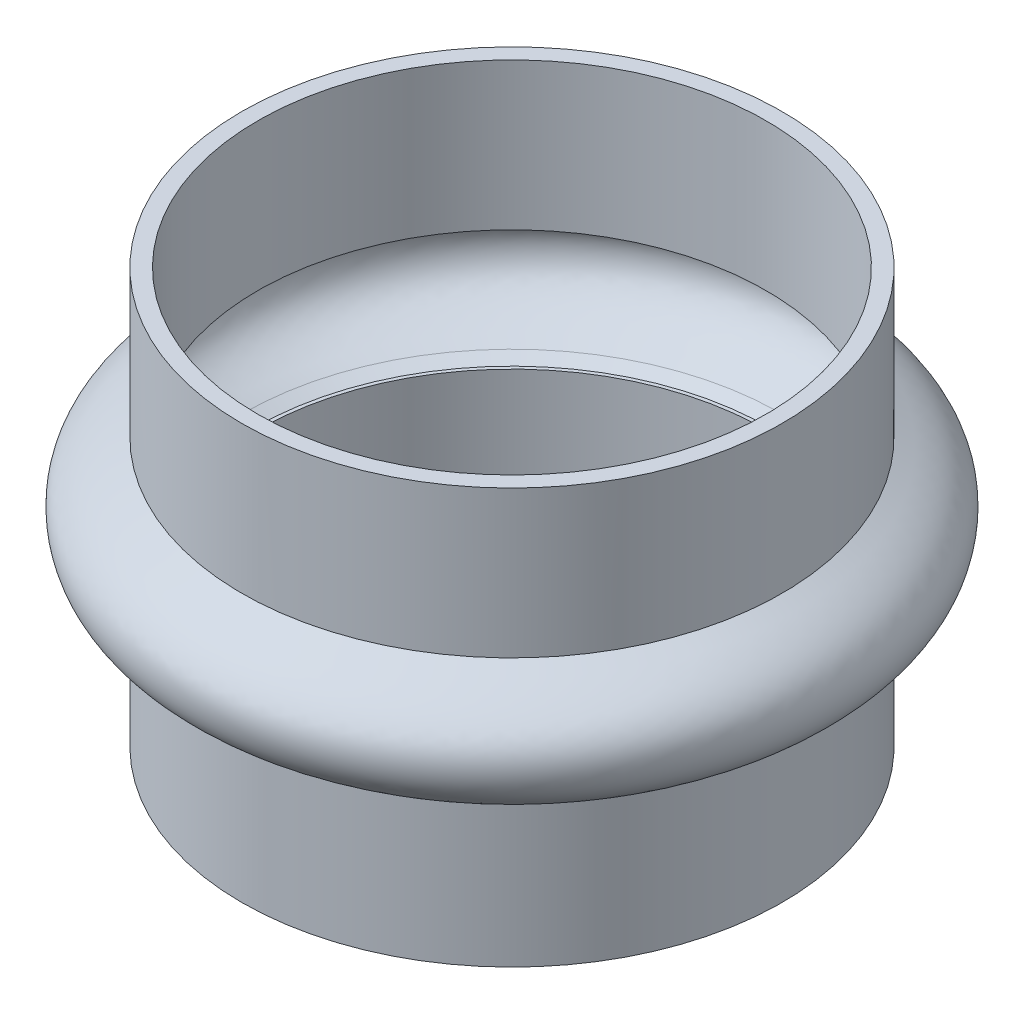
SolidWorks part; units mm, degrees
ref_plane "Front Plane" through (0, 0, 0) normal (0, 0, 1) x (1, 0, 0)
ref_plane "Top Plane" through (0, 0, 0) normal (0, 1, 0) x (1, 0, 0)
ref_plane "Right Plane" through (0, 0, 0) normal (1, 0, 0) x (0, 0, -1)
sketch "Sketch1" plane through (0, 0, 0) normal (0, 0, 1) x (1, 0, 0)
  line L0 (-921.4581, 1439.0368) -> (211.8752, 1439.0368) construction
  line L1 (-99.3333, 446.5) -> (103.3333, 446.5) construction
  line L2 (3.2388, 58.9758) -> (39.625, 58.9758) construction
  line L3 (25.6903, 76.5393) -> (25.6903, 40.3207) construction
  line L4 (7.3253, 63.4119) -> (25.6903, 63.4119) construction
  line L5 (7.3253, 63.4119) -> (25.6903, 76.5393) construction
  line L6 (7.3253, 63.4119) -> (8.411, 63.4119)
  line L7 (8.411, 63.4119) -> (7.5555, 62.9681)
  line L8 (7.3735, 55.6488) -> (8.166, 55.2112)
  line L9 (8.166, 55.2112) -> (7.1318, 55.2112)
  spline S0 degree 3 poles (7.3253, 63.4119) (6.0111, 62.7301) (2.9718, 61.4252) (3.4634, 56.9126) (5.9426, 55.8679) (7.1318, 55.2112) knots 0 0 0 0 0.43 0.624673 1 1 1 1
  spline S1 degree 1 poles (7.5555, 62.9681) (7.3735, 55.6488) knots 0 0 1 1 construction
  spline S2 degree 3 poles (7.5555, 62.9681) (7.35, 62.8614) (6.9471, 62.6604) (6.0541, 62.2018) (4.9545, 61.5406) (4.1595, 60.7257) (3.8436, 60.0138) (3.7346, 59.1782) (3.99, 58.0647) (4.8318, 57.1066) (6.086, 56.3114) (6.9493, 55.8831) (7.3735, 55.6488) knots 0 0 0 0 0.0625 0.125 0.25 0.375 0.4375 0.5 0.625 0.75 0.875 1 1 1 1
  dimension "D1" = 36.3862
  dimension "D2" = 0.5
  dimension "D3" = 18.365
revolve "Revolve1" add sketch "Sketch1" angle 360 about L3
ref_plane "Plane1" through (0, 59.3115, 0) normal (0, 1, 0) x (1, 0, 0)
sketch "Sketch2" plane through (0, 63.4119, 0) normal (0, 1, 0) x (1, 0, 0)
  circle A0 centre (25.6903, 0) radius 18.365
  circle A1 centre (25.6903, 0) radius 18.365 construction
  circle A2 centre (25.6903, 0) radius 17.2793
  circle A3 centre (25.6903, 0) radius 17.2793 construction
extrude "Boss-Extrude1" add sketch "Sketch2" along normal blind 10
mirror "Mirror1" about plane through (0, 59.3115, 0) normal (0, 1, 0) of "Boss-Extrude1"
